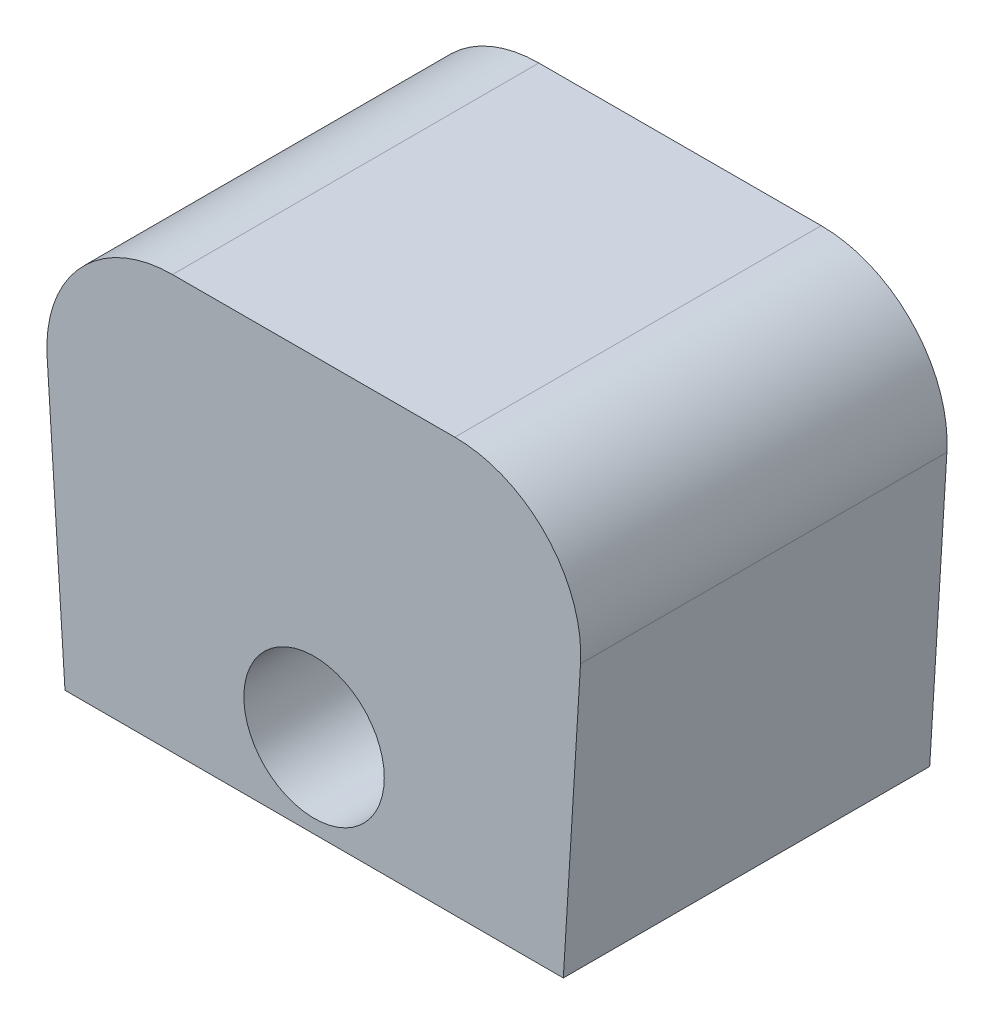
SolidWorks part; units mm, degrees
ref_plane "Front Plane" through (0, 0, 0) normal (0, 0, 1) x (1, 0, 0)
ref_plane "Top Plane" through (0, 0, 0) normal (0, 1, 0) x (1, 0, 0)
ref_plane "Right Plane" through (0, 0, 0) normal (1, 0, 0) x (0, 0, -1)
sketch "Sketch2" plane through (0, 0, 0) normal (0, 0, 1) x (1, 0, 0)
  line L0 (-5.0322, -170.1408) -> (-3.337, -142.4651)
  line L1 (-7.1446, -138.4222) -> (-15.6987, -138.4328)
  line L2 (-19.4962, -142.4852) -> (-17.7322, -170.1565)
  circle A0 centre (-11.4092, -148.4285) radius 2.127
  arc A1 (-17.7322, -170.1565) -> (-5.0322, -170.1408) centre (-11.3824, -170.0171) ccw
  arc A2 (-3.337, -142.4651) -> (-7.1446, -138.4222) centre (-7.1399, -142.2322) ccw
  arc A3 (-15.6987, -138.4328) -> (-19.4962, -142.4852) centre (-15.6939, -142.2428) ccw
  circle A4 centre (-11.3808, -171.2885) radius 2.127
extrude "Boss-Extrude1" add sketch "Sketch2" along normal blind 11.0998
sketch "Sketch3" plane through (0, 0, 11.0998) normal (0, 0, 1) x (1, 0, 0)
  line L1 (-21.7956, -181.8253) -> (2.3149, -181.8253)
  line L2 (-21.7956, -181.8253) -> (-21.7956, -150.9685)
  line L3 (-21.7956, -150.9685) -> (2.3149, -150.9685)
  line L4 (2.3149, -181.8253) -> (2.3149, -150.9685)
  circle A0 centre (-11.4092, -148.4285) radius 2.127 construction
  dimension "D1" = 2.54
extrude "Cut-Extrude1" cut sketch "Sketch3" against normal blind 11.0998
